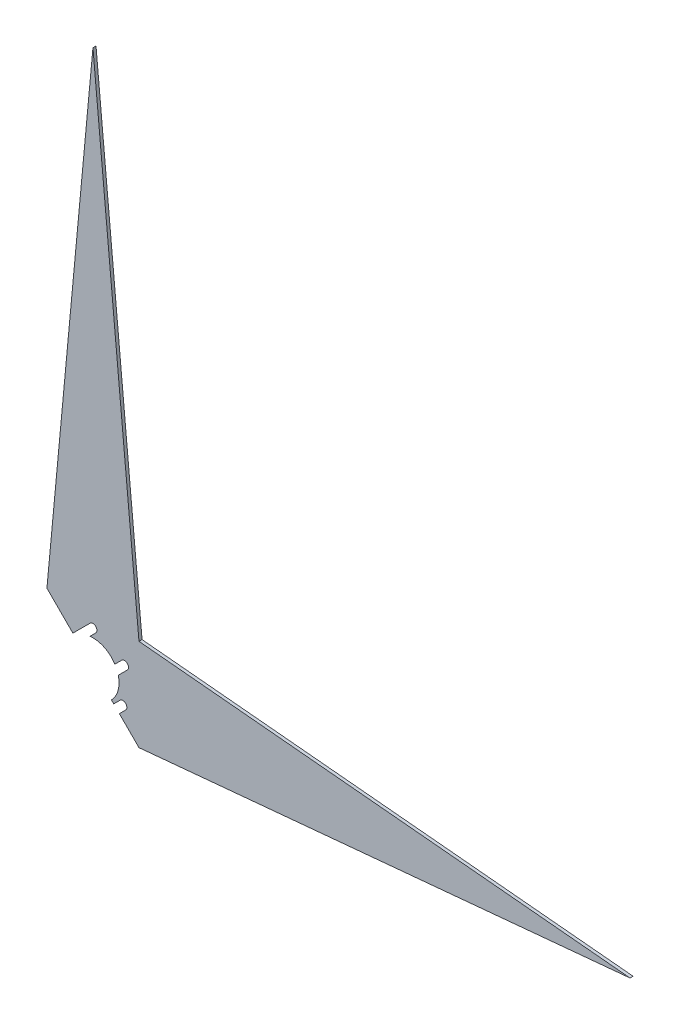
SolidWorks part; units mm, degrees
ref_plane "前视基准面" through (0, 0, 0) normal (0, 0, 1) x (1, 0, 0)
ref_plane "上视基准面" through (0, 0, 0) normal (0, 1, 0) x (1, 0, 0)
ref_plane "右视基准面" through (0, 0, 0) normal (1, 0, 0) x (0, 0, -1)
sketch "草图1" plane through (0, 0, 0) normal (0, 0, 1) x (1, 0, 0)
  line L0 (0, 0) -> (47.14, -47.14) construction
  line L1 (0, 0) -> (47.14, 0) construction
  line L4 (47.14, 0) -> (47.14, -47.14) construction
  line L5 (23.57, -23.57) -> (373.57, -23.57) construction
  line L6 (23.57, -23.57) -> (23.57, 326.43) construction
  line L7 (53.57, -53.57) -> (373.57, -23.57)
  line L8 (-6.43, -53.57) -> (53.57, -53.57)
  line L9 (-6.43, -53.57) -> (-6.43, 6.43)
  line L10 (-6.43, 6.43) -> (53.57, 6.43) construction
  line L11 (53.57, -53.57) -> (53.57, 6.43) construction
  line L12 (-6.43, -53.57) -> (53.57, 6.43) construction
  line L13 (-6.43, 6.43) -> (53.57, -53.57) construction
  line L14 (373.57, -23.57) -> (53.57, 6.43)
  line L15 (53.57, 6.43) -> (23.57, 326.43)
  line L16 (23.57, 326.43) -> (-6.43, 6.43)
  line L17 (23.57, -23.57) -> (59.7673, -23.57) construction
  line L18 (23.57, -23.57) -> (62.8424, -46.2439) construction
  circle A5 centre (23.57, -23.57) radius 23.75 construction
  circle A6 centre (23.57, -23.57) radius 22.5 construction
  circle A7 centre (23.57, -47.32) radius 2.6
  circle A8 centre (3.0019, -11.695) radius 2.6
  circle A9 centre (44.1381, -11.695) radius 2.6
  circle A10 centre (43.0556, -34.82) radius 2.6
  circle A11 centre (4.0844, -34.82) radius 2.6
  circle A12 centre (23.57, -1.07) radius 2.6
  circle A13 centre (23.57, -23.57) radius 17
  dimension "D5" = 47.5
  dimension "D6" = 45
  dimension "D7" = 5.2
  dimension "D9" = 5.2
  dimension "D1" = 350
  dimension "D4" = 60
  dimension "D8" = 30
extrude "凸台-拉伸1" add sketch "草图1" along normal blind 2
sketch "草图2" plane through (0, 0, 2) normal (0, 0, 1) x (1, 0, 0)
  line L0 (-6.43, 6.43) -> (53.57, -53.57) construction
  line L1 (53.57, -53.57) -> (-6.43, -53.57)
  line L2 (-6.43, -53.57) -> (-6.43, 6.43)
  line L3 (53.57, 6.43) -> (-6.43, -53.57) construction
  line L4 (25.4085, -2.9085) -> (14.1585, -14.1585)
  line L5 (21.7315, 0.7685) -> (10.4815, -10.4815)
  line L6 (45.9766, -13.5335) -> (29.755, -29.755)
  line L7 (42.2996, -9.8565) -> (26.0781, -26.0781)
  line L8 (44.894, -36.6585) -> (40.7763, -40.7763)
  line L9 (41.2171, -32.9815) -> (37.0993, -37.0993)
  line L10 (-6.43, 6.43) -> (10.4815, -10.4815)
  line L11 (14.1585, -14.1585) -> (26.0781, -26.0781)
  line L12 (29.755, -29.755) -> (37.0993, -37.0993)
  line L13 (40.7763, -40.7763) -> (53.57, -53.57)
  line L14 (21.7315, 0.7685) -> (25.4085, -2.9085)
  line L15 (42.2996, -9.8565) -> (45.9766, -13.5335)
  line L16 (41.2171, -32.9815) -> (44.894, -36.6585)
  circle A0 centre (23.57, -1.07) radius 2.6 construction
  circle A1 centre (44.1381, -11.695) radius 2.6 construction
  circle A2 centre (43.0556, -34.82) radius 2.6 construction
  point P28 (42.8352, -38.7174)
  dimension "D1" = 5.2
  dimension "D2" = 5.2
  dimension "D3" = 5.2
extrude "切除-拉伸2" cut sketch "草图2" against normal blind 2
